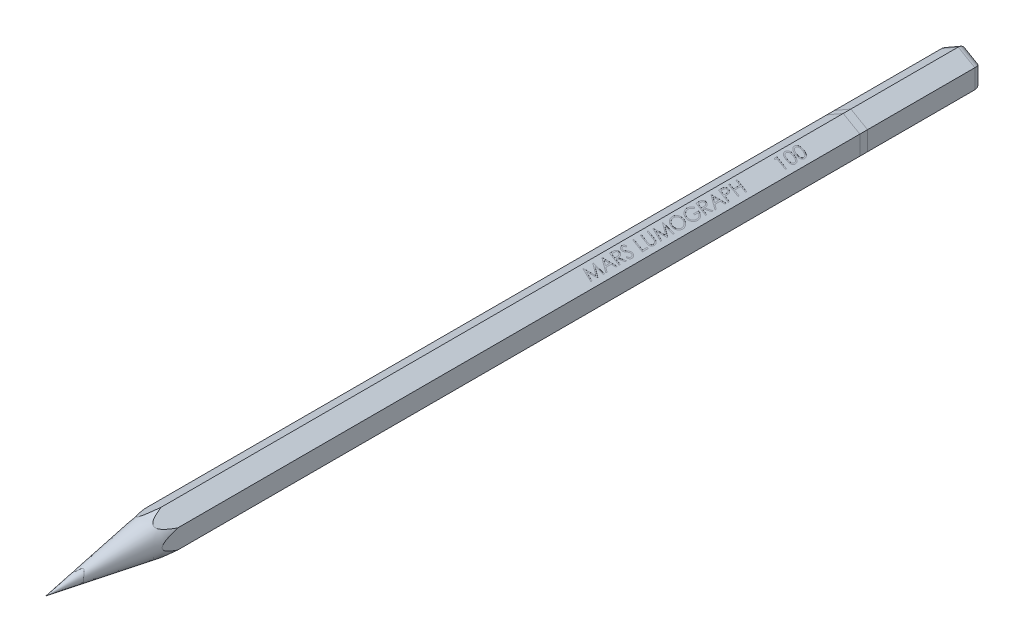
SolidWorks part; units mm, degrees
material "Mahogany"
ref_plane "Front Plane" through (0, 0, 0) normal (0, 0, 1) x (1, 0, 0)
ref_plane "Top Plane" through (0, 0, 0) normal (0, 1, 0) x (1, 0, 0)
ref_plane "Right Plane" through (0, 0, 0) normal (1, 0, 0) x (0, 0, -1)
sketch "Sketch1" plane through (0, 0, 0) normal (1, 0, 0) x (0, 0, -1)
  line L0 (0, 0) -> (240, 0)
  line L1 (240, 0) -> (240, 5)
  line L2 (240, 5) -> (30, 5)
  line L3 (30, 5) -> (0, 0)
  dimension "D1" = 30
  dimension "D2" = 240
  dimension "D3" = 5
revolve "Revolve1" add sketch "Sketch1" angle 360 about L0
sketch "Sketch2" plane through (0, 0, -240) normal (0, 0, -1) x (-1, 0, 0)
  line L1 (0, -5) -> (4.3301, -2.5)
  line L2 (4.3301, -2.5) -> (4.3301, 2.5)
  line L3 (4.3301, 2.5) -> (0, 5)
  line L4 (0, 5) -> (-4.3301, 2.5)
  line L5 (-4.3301, 2.5) -> (-4.3301, -2.5)
  line L6 (-4.3301, -2.5) -> (0, -5)
  circle A0 centre (0, 0) radius 4.3301 construction
extrude "Cut-Extrude1" cut sketch "Sketch2" against normal through all flip side to cut
sketch "Sketch3" plane through (0, 0, 0) normal (0, 1, 0) x (1, 0, 0)
  line L0 (-4.3301, 25.9808) -> (0, 0) construction
  spline S0 degree 3 poles (-2.0202, 8.7868) (-3.2246, 12.0759) (-2.2086, 10.5612) (-0.2539, 7.0097) (-0.0271, 12.138) (3.3707, 4.1303) (4.1028, 9.2151) knots 0 0 0 0 0.348169 0.500642 0.635482 1 1 1 1
  dimension "D1" = 8
split line "Split Line1"
fillet "Fillet3" radius 2 6 edges at (2.1651, 3.75, -240) (-2.1651, 3.75, -240) (-4.3301, 0, -240) (-2.1651, -3.75, -240) (2.1651, -3.75, -240) (4.3301, 0, -240)
sketch "Sketch7" plane through (0, 0, 0) normal (1, 0, 0) x (0, 0, -1)
  line L0 (210, 8.0894) -> (210, -9.8199)
  line L1 (208, 8.0894) -> (208, -9.8199)
  line L2 (240, 1.3453) -> (240, -1.3453) construction
  dimension "D1" = 2
  dimension "D2" = 30
split line "Split Line2"
sketch "Sketch9" plane through (2.1651, 3.75, 0) normal (0.5, 0.866, 0) x (0.866, -0.5, 0)
  line L0 (1.2144, 208) -> (1.2144, 109.3623) construction
  line L1 (2.5, 208) -> (-2.5, 208) construction
  line L2 (1.2144, 109.3623) -> (1.2144, 86.9103) construction
  text T0 "                               MARS LUMOGRAPH       100" font "Century Gothic" height in points 11
extrude "Cut-Extrude2" cut sketch "Sketch9" against normal blind 0.02
